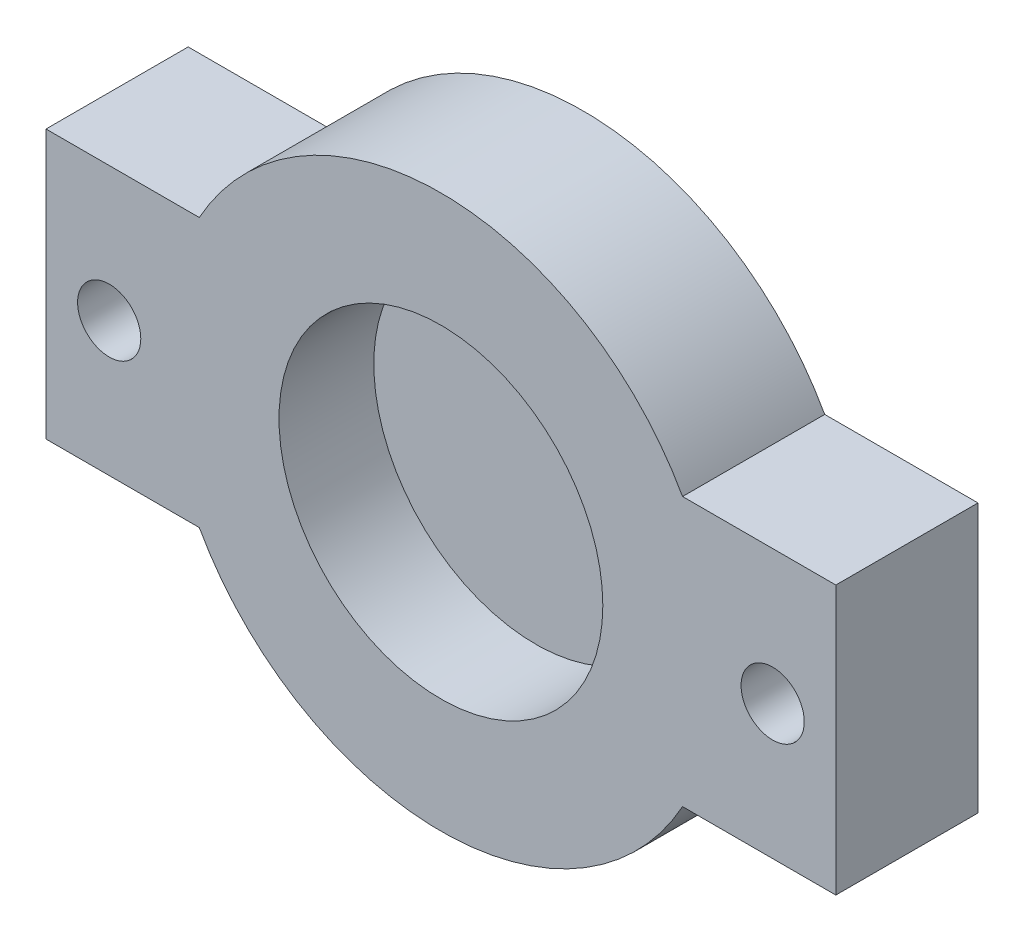
SolidWorks part; units mm, degrees
ref_plane "Front Plane" through (0, 0, 0) normal (0, 0, 1) x (1, 0, 0)
ref_plane "Top Plane" through (0, 0, 0) normal (0, 1, 0) x (1, 0, 0)
ref_plane "Right Plane" through (0, 0, 0) normal (1, 0, 0) x (0, 0, -1)
sketch "Sketch1" plane through (0, 0, 0) normal (0, 0, 1) x (1, 0, 0)
  line L0 (0, -55) -> (0, 55) construction
  line L1 (-25, -8.5) -> (25, -8.5)
  line L2 (-25, -8.5) -> (-25, 8.5)
  line L3 (-25, 8.5) -> (25, 8.5)
  line L4 (25, -8.5) -> (25, 8.5)
  line L5 (-25, -8.5) -> (25, 8.5) construction
  line L6 (-25, 8.5) -> (25, -8.5) construction
  circle A0 centre (0, 0) radius 17.5
  circle A1 centre (21, 0) radius 2
  circle A2 centre (-21, 0) radius 2
  dimension "D1" = 35
  dimension "D4" = 21
  dimension "D2" = 17
  dimension "D3" = 50
extrude "Boss-Extrude3" add sketch "Sketch1" along normal blind 9 contours A0 L3 L2 L1 A2 | L3 A0 | L3 A0 L1 | L1 A0 | A0 L1 L4 L3 A1
sketch "Sketch2" plane through (0, 0, 9) normal (0, 0, 1) x (1, 0, 0)
  circle A0 centre (0, 0) radius 10.25
  dimension "D1" = 20.5
extrude "Cut-Extrude1" cut sketch "Sketch2" against normal blind 6
